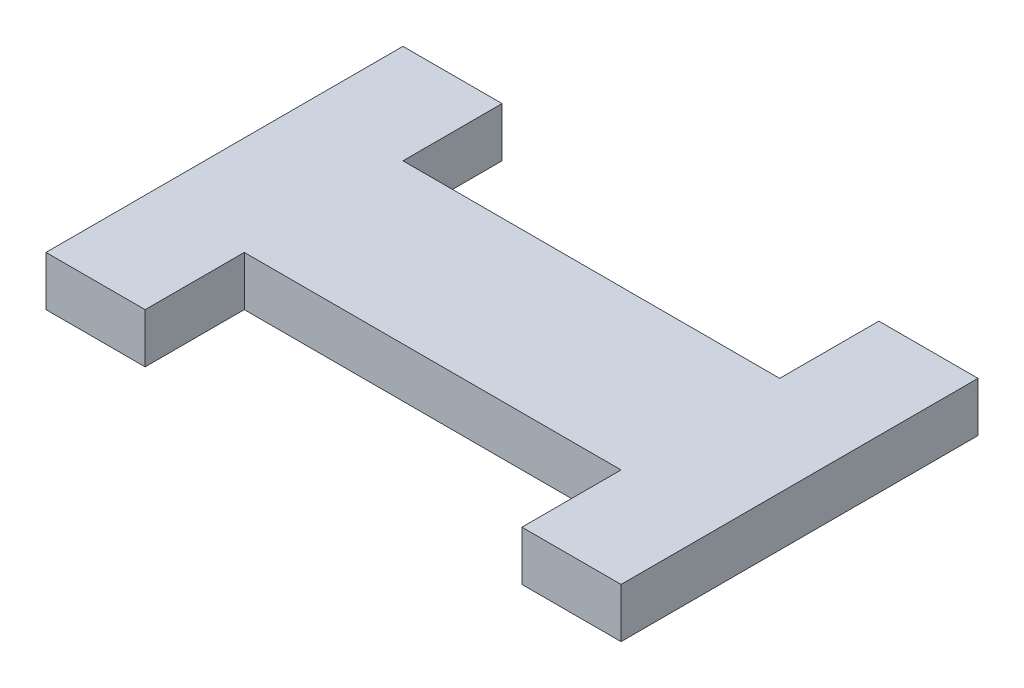
SolidWorks part; units mm, degrees
ref_plane "Front Plane" through (0, 0, 0) normal (0, 0, 1) x (1, 0, 0)
ref_plane "Top Plane" through (0, 0, 0) normal (0, 1, 0) x (1, 0, 0)
ref_plane "Right Plane" through (0, 0, 0) normal (1, 0, 0) x (0, 0, -1)
sketch "Sketch1" plane through (0, 0, 0) normal (0, 1, 0) x (1, 0, 0)
  line L1 (-18.415, 11.43) -> (18.415, 11.43)
  line L2 (-18.415, 11.43) -> (-18.415, -11.43)
  line L3 (-18.415, -11.43) -> (18.415, -11.43)
  line L4 (18.415, 11.43) -> (18.415, -11.43)
  line L5 (-18.415, 11.43) -> (18.415, -11.43) construction
  line L6 (-18.415, -11.43) -> (18.415, 11.43) construction
  point P0 (0, 0)
  dimension "D1" = 36.83
  dimension "D2" = 22.86
extrude "Boss-Extrude1" add sketch "Sketch1" along normal blind 3.175
sketch "Sketch2" plane through (0, 3.175, 0) normal (0, 1, 0) x (1, 0, 0)
  line L0 (18.415, 11.43) -> (-18.415, 11.43) construction
  line L1 (-12.065, 11.43) -> (12.065, 11.43)
  line L2 (-12.065, 11.43) -> (-12.065, 5.08)
  line L3 (-12.065, 5.08) -> (12.065, 5.08)
  line L4 (12.065, 11.43) -> (12.065, 5.08)
  line L5 (-18.415, -11.43) -> (18.415, -11.43) construction
  line L6 (12.065, -11.43) -> (-12.065, -11.43)
  line L7 (12.065, -11.43) -> (12.065, -5.08)
  line L8 (12.065, -5.08) -> (-12.065, -5.08)
  line L9 (-12.065, -11.43) -> (-12.065, -5.08)
  line L10 (-18.415, 11.43) -> (-18.415, -11.43) construction
  line L11 (18.415, -11.43) -> (18.415, 11.43) construction
  dimension "D1" = 6.35
  dimension "D2" = 6.35
  dimension "D3" = 6.35
extrude "Cut-Extrude1" cut sketch "Sketch2" against normal through all
